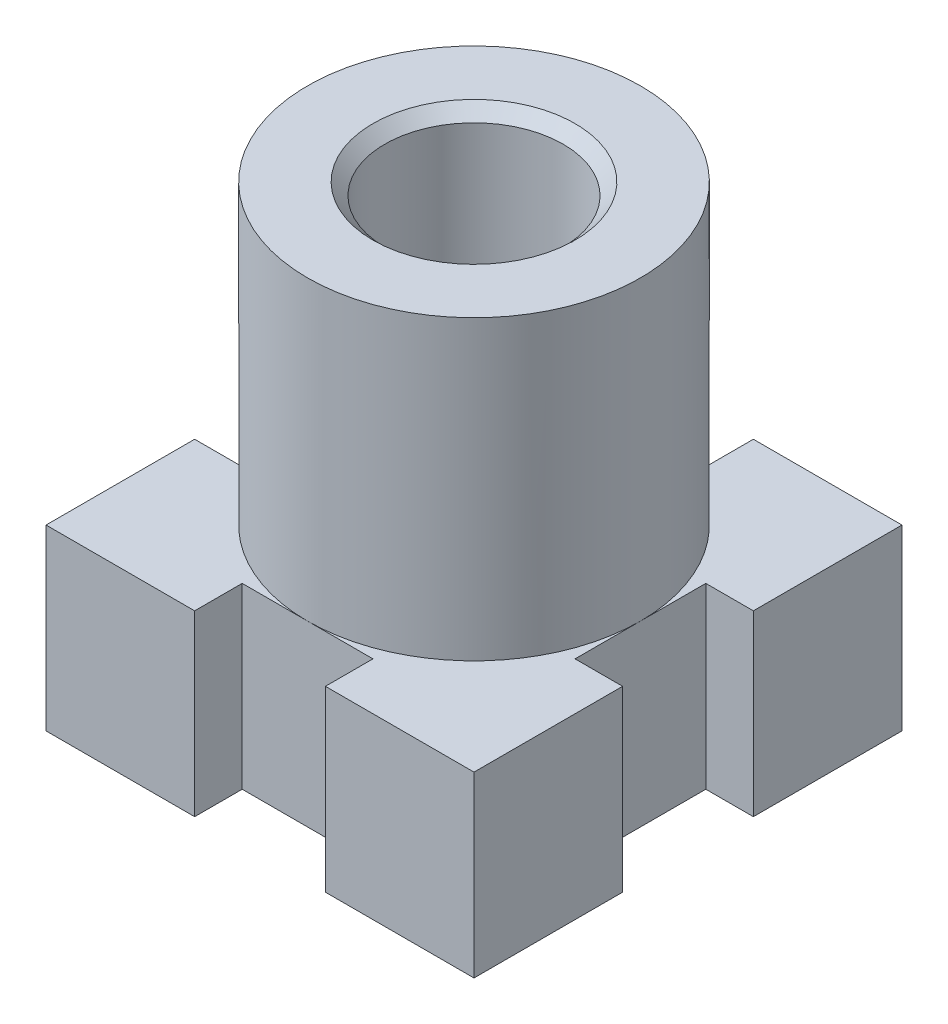
SolidWorks part; units mm, degrees
ref_plane "Front Plane" through (0, 0, 0) normal (0, 0, 1) x (1, 0, 0)
ref_plane "Top Plane" through (0, 0, 0) normal (0, 1, 0) x (1, 0, 0)
ref_plane "Right Plane" through (0, 0, 0) normal (1, 0, 0) x (0, 0, -1)
sketch "Sketch1" plane through (0, 0, 0) normal (0, 1, 0) x (1, 0, 0)
  line L20 (9.144, 2.794) -> (7.112, 2.794)
  line L21 (7.112, 2.794) -> (7.112, -2.794)
  line L22 (7.112, -2.794) -> (9.144, -2.794)
  line L23 (9.144, 9.144) -> (2.794, 9.144)
  line L24 (-9.144, 9.144) -> (-9.144, 2.794)
  line L25 (-9.144, -9.144) -> (-2.794, -9.144)
  line L26 (9.144, -9.144) -> (9.144, -2.794)
  line L27 (-2.794, -7.112) -> (-2.794, -9.144)
  line L28 (2.794, -9.144) -> (2.794, -7.112)
  line L29 (2.794, -7.112) -> (-2.794, -7.112)
  line L30 (-7.112, 2.794) -> (-9.144, 2.794)
  line L31 (-9.144, -2.794) -> (-7.112, -2.794)
  line L32 (-7.112, -2.794) -> (-7.112, 2.794)
  line L33 (2.794, 7.112) -> (2.794, 9.144)
  line L34 (-2.794, 9.144) -> (-2.794, 7.112)
  line L35 (-2.794, 7.112) -> (2.794, 7.112)
  line L36 (-2.794, 9.144) -> (-9.144, 9.144)
  line L37 (9.144, 2.794) -> (9.144, 9.144)
  line L38 (2.794, -9.144) -> (9.144, -9.144)
  line L39 (-9.144, -2.794) -> (-9.144, -9.144)
  dimension "D1" = 2.794
  dimension "D2" = 7.112
  dimension "D3" = 9.144
  dimension "D4" = 2.794
  dimension "D5" = 2.794
extrude "Boss-Extrude1" add sketch "Sketch1" along normal blind 7.62
sketch "Sketch2" plane through (0, 7.62, 0) normal (0, 1, 0) x (1, 0, 0)
  circle A0 centre (0, 0) radius 7.112
  circle A1 centre (0, 0) radius 3.81
  dimension "D1" = 14.224
  dimension "D2" = 7.62
extrude "Boss-Extrude2" add sketch "Sketch2" along normal blind 12.7
chamfer "Chamfer1" distance 0.508 1 edges at (0, 20.32, 3.81)
